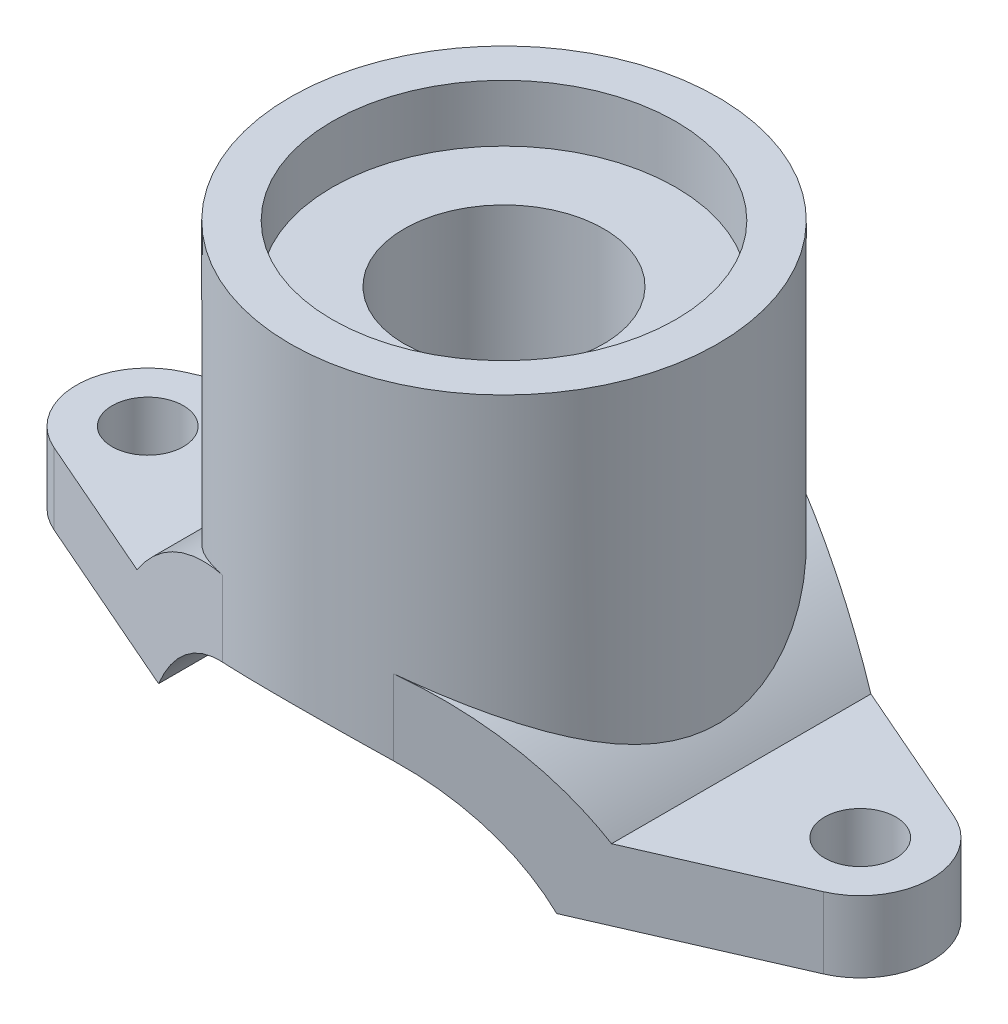
SolidWorks part; units mm, degrees
ref_plane "Front Plane" through (0, 0, 0) normal (0, 0, 1) x (1, 0, 0)
ref_plane "Top Plane" through (0, 0, 0) normal (0, 1, 0) x (1, 0, 0)
ref_plane "Right Plane" through (0, 0, 0) normal (1, 0, 0) x (0, 0, -1)
sketch "Sketch1" plane through (0, 0, 0) normal (0, 0, 1) x (1, 0, 0)
  line L0 (0, 0) -> (0, -65470.3283) construction
  line L1 (0, 0) -> (-65470.3283, 0) construction
  line L3 (-150, 25) -> (150, 25)
  line L4 (-150, 25) -> (-150, 0)
  line L5 (-150, 0) -> (150, 0)
  line L6 (150, 25) -> (150, 0)
  arc A0 (-69.8498, 0) -> (69.8498, 0) centre (0, -39) cw
  arc A1 (-97.4885, 0) -> (97.4885, 0) centre (0, -39) cw
  dimension "D1" = 80
  dimension "D2" = 105
  dimension "D3" = 39
  dimension "D4" = 25
  dimension "D5" = 300
extrude "Boss-Extrude2" add sketch "Sketch1" along normal mid plane 150 contours L3 A1 L5 L6 | A1 L3 A0 L5 | A1 L3 A0 | A1 L5 A0 L3 | L5 A1 L3 L4
sketch "Sketch2" plane through (0, 0, 0) normal (0, 1, 0) x (1, 0, 0)
  line L0 (0, 0) -> (-50000, 0) construction
  line L1 (0, 0) -> (0, -50000) construction
  line L2 (135, -22.9129) -> (30, -68.7386)
  line L3 (135, 22.9129) -> (30, 68.7386)
  line L4 (-135, -22.9129) -> (-30, -68.7386)
  line L5 (-135, 22.9129) -> (-30, 68.7386)
  circle A0 centre (125, 0) radius 12.5
  arc A1 (135, -22.9129) -> (135, 22.9129) centre (125, 0) ccw
  circle A2 centre (-125, 0) radius 12.5
  arc A3 (-135, 22.9129) -> (-135, -22.9129) centre (-125, 0) ccw
  arc A4 (-30, -68.7386) -> (30, -68.7386) centre (0, 0) ccw
  arc A5 (30, 68.7386) -> (-30, 68.7386) centre (0, 0) ccw
  point P2 (0, 0)
  point P22 (0, 0)
  dimension "D1" = 25
  dimension "D2" = 50
  dimension "D3" = 25
  dimension "D4" = 50
  dimension "D5" = 250
  dimension "D6" = 150
extrude "Cut-Extrude3" cut sketch "Sketch2" along normal blind 150 flip side to cut
ref_plane "Plane1" through (0, 150, 0) normal (0, 1, 0) x (1, 0, 0)
sketch "Sketch3" plane through (0, 150, 0) normal (0, 1, 0) x (1, 0, 0)
  circle A0 centre (0, 0) radius 75
  dimension "D1" = 150
extrude "Boss-Extrude3" add sketch "Sketch3" against normal up to next
sketch "Sketch5" plane through (0, 0, 0) normal (0, 0, 1) x (1, 0, 0)
  line L0 (0, 0) -> (0, -50000) construction
  line L1 (0, 150) -> (60.2541, 150)
  line L2 (60.2541, 150) -> (60.2541, 130)
  line L3 (60.2541, 130) -> (35, 130)
  line L4 (35, 130) -> (35, 0)
  line L5 (35, 0) -> (0, 0)
  line L6 (0, 0) -> (0, 150)
  line L7 (66.2795, 150) -> (-66.2795, 150) construction
  dimension "D1" = 120.5081
  dimension "D2" = 20
  dimension "D3" = 70
revolve "Cut-Revolve3" cut sketch "Sketch5" angle 360 about L0
